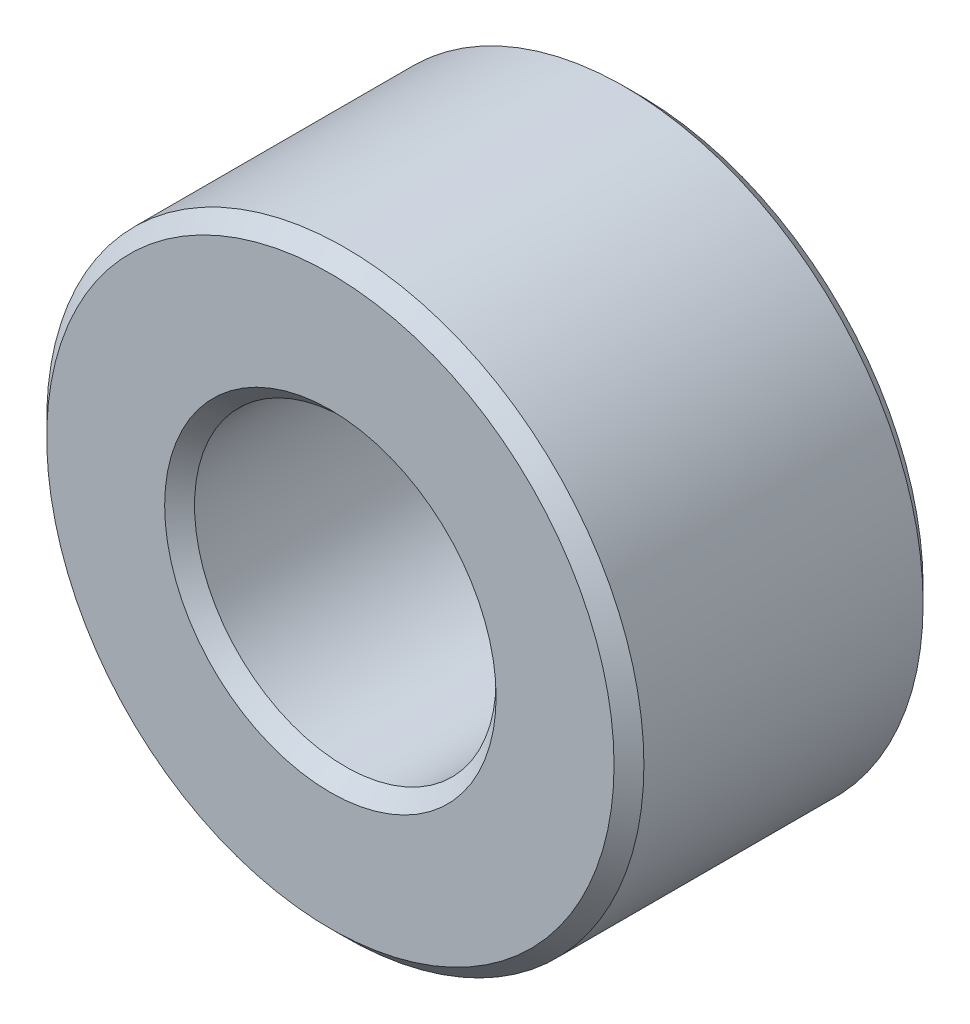
SolidWorks part; units mm, degrees
material "ASTM A36 Aço"
ref_plane "Plano frontal" through (0, 0, 0) normal (0, 0, 1) x (1, 0, 0)
ref_plane "Plano superior" through (0, 0, 0) normal (0, 1, 0) x (1, 0, 0)
ref_plane "Plano direito" through (0, 0, 0) normal (1, 0, 0) x (0, 0, -1)
sketch "Esboço1" plane through (0, 0, 0) normal (0, 0, 1) x (1, 0, 0)
  circle A0 centre (0, 0) radius 5.05
  circle A1 centre (0, 0) radius 10
  dimension "D1" = 10.1
  dimension "D2" = 20
extrude "Ressalto-extrusão1" add sketch "Esboço1" along normal mid plane 10.35
chamfer "Chanfro1" distance 0.5 angle 45 4 edges at (5.05, 0, -5.175) (10, 0, -5.175) (5.05, 0, 5.175) (10, 0, 5.175)
sketch "Esboço2" plane through (0, 0, 0) normal (0, 1, 0) x (1, 0, 0)
  line L0 (9.5, 5.175) -> (-9.5, 5.175) construction
  line L1 (-7.5, 5.175) -> (-10, 5.175)
  line L2 (-7.5, 5.175) -> (-7.5, -1.375)
  line L3 (-7.5, -1.375) -> (-10, -1.375)
  line L4 (-10, 5.175) -> (-10, -1.375)
  line L5 (-10, 4.675) -> (-10, -4.675) construction
  line L6 (10, -4.675) -> (10, 4.675) construction
  line L7 (7.5, 5.175) -> (10, 5.175)
  line L8 (7.5, 5.175) -> (7.5, -1.375)
  line L9 (7.5, -1.375) -> (10, -1.375)
  line L10 (10, 5.175) -> (10, -1.375)
  line L11 (-9.5, -5.175) -> (9.5, -5.175) construction
  dimension "D1" = 15
  dimension "D2" = 3.8
